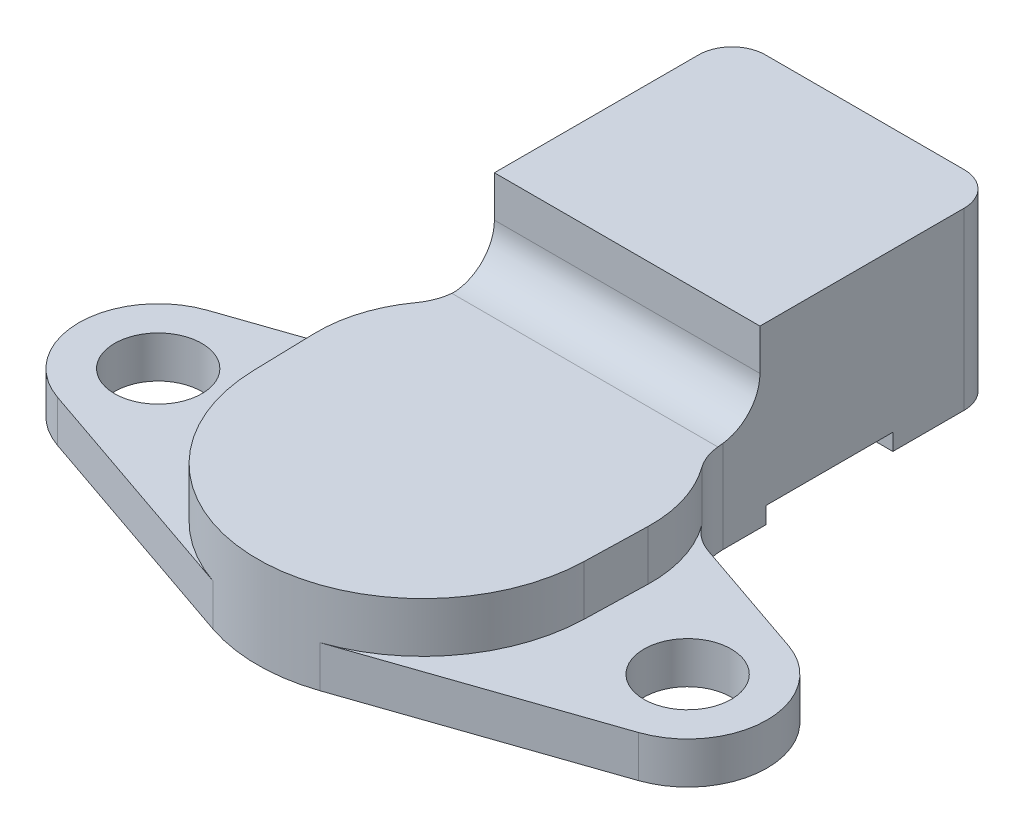
SolidWorks part; units mm, degrees
ref_plane "Front Plane" through (0, 0, 0) normal (0, 0, 1) x (1, 0, 0)
ref_plane "Top Plane" through (0, 0, 0) normal (0, 1, 0) x (1, 0, 0)
ref_plane "Right Plane" through (0, 0, 0) normal (1, 0, 0) x (0, 0, -1)
sketch "Sketch1" plane through (0, 0, 0) normal (0, 1, 0) x (1, 0, 0)
  line L30 (-6.7564, 4.8768) -> (-6.7564, 12.6)
  line L31 (-6.7564, 12.6) -> (-7.9629, 12.6)
  line L32 (-7.9629, 12.6) -> (-7.9629, 10.0193)
  line L33 (-10.1067, 7.0165) -> (-17.4219, 4.5043)
  line L34 (-17.4219, -4.5043) -> (-3.2216, -9.3809)
  line L35 (3.2216, -9.3809) -> (17.4219, -4.5043)
  line L36 (17.4219, 4.5043) -> (10.1067, 7.0165)
  line L37 (7.9629, 10.0193) -> (7.9629, 12.6)
  line L38 (7.9629, 12.6) -> (6.7564, 12.6)
  line L39 (6.7564, 12.6) -> (6.7564, 4.8768)
  line L46 (-6.7564, 20.22) -> (-6.7564, 24.25)
  line L47 (-6.7564, 24.25) -> (6.7564, 24.25)
  line L48 (6.7564, 24.25) -> (6.7564, 20.22)
  line L49 (6.7564, 20.22) -> (7.9629, 20.22)
  line L50 (7.9629, 20.22) -> (7.9629, 25.5)
  line L51 (7.9629, 25.5) -> (-7.9629, 25.5)
  line L52 (-7.9629, 25.5) -> (-7.9629, 20.22)
  line L53 (-7.9629, 20.22) -> (-6.7564, 20.22)
  circle A10 centre (15.875, 0) radius 2.6162
  circle A12 centre (-15.875, 0) radius 2.6162
  arc A28 (-6.7965, 4.8183) -> (-6.7564, 4.8768) centre (-8.6614, 6.1404) ccw
  arc A29 (-10.1067, 7.0165) -> (-7.9629, 10.0193) centre (-11.1379, 10.0193) ccw
  arc A30 (-17.4219, 4.5043) -> (-17.4219, -4.5043) centre (-15.875, 0) ccw
  arc A31 (-3.2216, -9.3809) -> (3.2216, -9.3809) centre (0, 0) ccw
  arc A32 (17.4219, -4.5043) -> (17.4219, 4.5043) centre (15.875, 0) ccw
  arc A33 (7.9629, 10.0193) -> (10.1067, 7.0165) centre (11.1379, 10.0193) ccw
  arc A34 (6.7564, 4.8768) -> (6.7965, 4.8183) centre (8.6614, 6.1404) ccw
  arc A35 (-6.7965, 4.8183) -> (6.7965, 4.8183) centre (0, 0) ccw
sketch "Sketch3" plane through (0, 0, 0) normal (0, 1, 0) x (1, 0, 0)
  line L0 (6.7564, 24.25) -> (6.7564, 20.22) construction
  line L1 (6.7564, 20.22) -> (7.9629, 20.22) construction
  line L2 (7.9629, 20.22) -> (7.9629, 25.5) construction
  line L3 (7.9629, 25.5) -> (-7.9629, 25.5) construction
  line L4 (-7.9629, 25.5) -> (-7.9629, 20.22) construction
  line L5 (-7.9629, 20.22) -> (-6.7564, 20.22) construction
  line L6 (-6.7564, 20.22) -> (-6.7564, 24.25) construction
  line L7 (-6.7564, 24.25) -> (6.7564, 24.25) construction
  line L8 (6.7564, 12.6) -> (6.7564, 4.8768) construction
  line L9 (7.9629, 12.6) -> (6.7564, 12.6) construction
  line L10 (7.9629, 10.0193) -> (7.9629, 12.6) construction
  line L11 (17.4219, 4.5043) -> (10.1067, 7.0165) construction
  line L12 (3.2216, -9.3809) -> (17.4219, -4.5043) construction
  line L13 (-17.4219, -4.5043) -> (-3.2216, -9.3809) construction
  line L14 (-10.1067, 7.0165) -> (-17.4219, 4.5043) construction
  line L15 (-7.9629, 12.6) -> (-7.9629, 10.0193) construction
  line L16 (-6.7564, 12.6) -> (-7.9629, 12.6) construction
  line L17 (-6.7564, 4.8768) -> (-6.7564, 12.6) construction
  line L18 (6.7564, 24.25) -> (6.7564, 20.22)
  line L19 (6.7564, 20.22) -> (7.9629, 20.22)
  line L20 (7.9629, 20.22) -> (7.9629, 25.5)
  line L21 (7.9629, 25.5) -> (-7.9629, 25.5)
  line L22 (-7.9629, 25.5) -> (-7.9629, 20.22)
  line L23 (-7.9629, 20.22) -> (-6.7564, 20.22)
  line L24 (-6.7564, 20.22) -> (-6.7564, 24.25)
  line L25 (-6.7564, 24.25) -> (6.7564, 24.25)
  line L26 (6.7564, 12.6) -> (6.7564, 4.8768)
  line L27 (7.9629, 12.6) -> (6.7564, 12.6)
  line L28 (7.9629, 10.0193) -> (7.9629, 12.6)
  line L29 (17.4219, 4.5043) -> (10.1067, 7.0165)
  line L30 (3.2216, -9.3809) -> (17.4219, -4.5043)
  line L31 (-17.4219, -4.5043) -> (-3.2216, -9.3809)
  line L32 (-10.1067, 7.0165) -> (-17.4219, 4.5043)
  line L33 (-7.9629, 12.6) -> (-7.9629, 10.0193)
  line L34 (-6.7564, 12.6) -> (-7.9629, 12.6)
  line L35 (-6.7564, 4.8768) -> (-6.7564, 12.6)
  circle A0 centre (-15.875, 0) radius 2.6162 construction
  circle A1 centre (15.875, 0) radius 2.6162 construction
  arc A2 (-6.7965, 4.8183) -> (6.7965, 4.8183) centre (0, 0) ccw construction
  arc A3 (6.7564, 4.8768) -> (6.7965, 4.8183) centre (8.6614, 6.1404) ccw construction
  arc A4 (7.9629, 10.0193) -> (10.1067, 7.0165) centre (11.1379, 10.0193) ccw construction
  arc A5 (17.4219, -4.5043) -> (17.4219, 4.5043) centre (15.875, 0) ccw construction
  arc A6 (-3.2216, -9.3809) -> (3.2216, -9.3809) centre (0, 0) ccw construction
  arc A7 (-17.4219, 4.5043) -> (-17.4219, -4.5043) centre (-15.875, 0) ccw construction
  arc A8 (-10.1067, 7.0165) -> (-7.9629, 10.0193) centre (-11.1379, 10.0193) ccw construction
  arc A9 (-6.7965, 4.8183) -> (-6.7564, 4.8768) centre (-8.6614, 6.1404) ccw construction
  circle A10 centre (-15.875, 0) radius 2.6162
  circle A11 centre (15.875, 0) radius 2.6162
  arc A12 (-6.7965, 4.8183) -> (6.7965, 4.8183) centre (0, 0) ccw
  arc A13 (6.7564, 4.8768) -> (6.7965, 4.8183) centre (8.6614, 6.1404) ccw
  arc A14 (7.9629, 10.0193) -> (10.1067, 7.0165) centre (11.1379, 10.0193) ccw
  arc A15 (17.4219, -4.5043) -> (17.4219, 4.5043) centre (15.875, 0) ccw
  arc A16 (-3.2216, -9.3809) -> (3.2216, -9.3809) centre (0, 0) ccw
  arc A17 (-17.4219, 4.5043) -> (-17.4219, -4.5043) centre (-15.875, 0) ccw
  arc A18 (-10.1067, 7.0165) -> (-7.9629, 10.0193) centre (-11.1379, 10.0193) ccw
  arc A19 (-6.7965, 4.8183) -> (-6.7564, 4.8768) centre (-8.6614, 6.1404) ccw
extrude "Boss-Extrude1" add sketch "Sketch3" along normal blind 1
sketch "Sketch4" plane through (0, 1, 0) normal (0, 1, 0) x (1, 0, 0)
  line L0 (-6.7564, 24.25) -> (6.7564, 24.25) construction
  line L1 (6.7564, 24.25) -> (6.7564, 20.22) construction
  line L3 (7.9629, 20.22) -> (7.9629, 25.5) construction
  line L4 (7.9629, 25.5) -> (-7.9629, 25.5) construction
  line L5 (-7.9629, 25.5) -> (-7.9629, 20.22) construction
  line L7 (-6.7564, 20.22) -> (-6.7564, 24.25) construction
  line L8 (-6.7564, 4.8768) -> (-6.7564, 12.6) construction
  line L10 (-7.9629, 12.6) -> (-7.9629, 10.0193) construction
  line L11 (-10.1067, 7.0165) -> (-17.4219, 4.5043) construction
  line L12 (-17.4219, -4.5043) -> (-3.2216, -9.3809) construction
  line L13 (3.2216, -9.3809) -> (17.4219, -4.5043) construction
  line L14 (17.4219, 4.5043) -> (10.1067, 7.0165) construction
  line L15 (7.9629, 10.0193) -> (7.9629, 12.6) construction
  line L17 (6.7564, 12.6) -> (6.7564, 4.8768) construction
  line L18 (-6.7564, 24.25) -> (6.7564, 24.25)
  line L19 (6.7564, 24.25) -> (6.7564, 20.22)
  line L21 (7.9629, 20.22) -> (7.9629, 25.5)
  line L22 (7.9629, 25.5) -> (-7.9629, 25.5)
  line L23 (-7.9629, 25.5) -> (-7.9629, 20.22)
  line L25 (-6.7564, 20.22) -> (-6.7564, 24.25)
  line L26 (-6.7564, 4.8768) -> (-6.7564, 12.6)
  line L28 (-7.9629, 12.6) -> (-7.9629, 10.0193)
  line L29 (-10.1067, 7.0165) -> (-17.4219, 4.5043)
  line L30 (-17.4219, -4.5043) -> (-3.2216, -9.3809)
  line L31 (3.2216, -9.3809) -> (17.4219, -4.5043)
  line L32 (17.4219, 4.5043) -> (10.1067, 7.0165)
  line L33 (7.9629, 10.0193) -> (7.9629, 12.6)
  line L35 (6.7564, 12.6) -> (6.7564, 4.8768)
  line L36 (7.9629, 12.6) -> (7.9629, 20.22)
  line L37 (6.7564, 20.22) -> (6.7564, 12.6)
  line L38 (-6.7564, 20.22) -> (-6.7564, 12.6)
  line L39 (-7.9629, 20.22) -> (-7.9629, 12.6)
  arc A0 (-6.7965, 4.8183) -> (-6.7564, 4.8768) centre (-8.6614, 6.1404) ccw construction
  circle A1 centre (15.875, 0) radius 2.6162
  circle A2 centre (15.875, 0) radius 2.6162
  circle A3 centre (-15.875, 0) radius 2.6162
  circle A4 centre (-15.875, 0) radius 2.6162
  arc A5 (-10.1067, 7.0165) -> (-7.9629, 10.0193) centre (-11.1379, 10.0193) ccw construction
  arc A6 (-17.4219, 4.5043) -> (-17.4219, -4.5043) centre (-15.875, 0) ccw construction
  arc A7 (-3.2216, -9.3809) -> (3.2216, -9.3809) centre (0, 0) ccw construction
  arc A8 (17.4219, -4.5043) -> (17.4219, 4.5043) centre (15.875, 0) ccw construction
  arc A9 (7.9629, 10.0193) -> (10.1067, 7.0165) centre (11.1379, 10.0193) ccw construction
  arc A10 (6.7564, 4.8768) -> (6.7965, 4.8183) centre (8.6614, 6.1404) ccw construction
  arc A11 (-6.7965, 4.8183) -> (6.7965, 4.8183) centre (0, 0) ccw construction
  arc A12 (-6.7965, 4.8183) -> (-6.7564, 4.8768) centre (-8.6614, 6.1404) ccw
  arc A13 (-10.1067, 7.0165) -> (-7.9629, 10.0193) centre (-11.1379, 10.0193) ccw
  arc A14 (-17.4219, 4.5043) -> (-17.4219, -4.5043) centre (-15.875, 0) ccw
  arc A15 (-3.2216, -9.3809) -> (3.2216, -9.3809) centre (0, 0) ccw
  arc A16 (17.4219, -4.5043) -> (17.4219, 4.5043) centre (15.875, 0) ccw
  arc A17 (7.9629, 10.0193) -> (10.1067, 7.0165) centre (11.1379, 10.0193) ccw
  arc A18 (6.7564, 4.8768) -> (6.7965, 4.8183) centre (8.6614, 6.1404) ccw
  arc A19 (-6.7965, 4.8183) -> (6.7965, 4.8183) centre (0, 0) ccw
  dimension "D1" = 0
  dimension "D2" = 0
extrude "Boss-Extrude2" add sketch "Sketch4" along normal blind 1.5
sketch "Sketch5" plane through (0, 2.5, 0) normal (0, 1, 0) x (1, 0, 0)
  line L0 (-9.9153, -0.2608) -> (-10.1067, 7.0165)
  line L1 (10.1067, 7.0165) -> (9.9153, -0.2608)
  line L3 (-6.7564, 24.25) -> (-6.7564, 4.8768)
  line L4 (6.7564, 24.25) -> (-6.7564, 24.25)
  line L5 (6.7564, 4.8768) -> (6.7564, 24.25)
  line L6 (-6.7564, 24.25) -> (-6.7564, 4.8768)
  line L7 (6.7564, 24.25) -> (-6.7564, 24.25)
  line L8 (6.7564, 4.8768) -> (6.7564, 24.25)
  line L15 (7.9629, 10.0193) -> (7.9629, 25.5)
  line L16 (7.9629, 25.5) -> (-7.9629, 25.5)
  line L17 (-7.9629, 25.5) -> (-7.9629, 10.0193)
  line L18 (-10.1067, 7.0165) -> (-17.4219, 4.5043)
  line L19 (-17.4219, -4.5043) -> (-3.2216, -9.3809)
  line L20 (3.2216, -9.3809) -> (17.4219, -4.5043)
  line L21 (17.4219, 4.5043) -> (10.1067, 7.0165)
  line L22 (7.9629, 10.0193) -> (7.9629, 25.5)
  line L23 (7.9629, 25.5) -> (-7.9629, 25.5)
  line L24 (-7.9629, 25.5) -> (-7.9629, 10.0193)
  line L25 (-10.1067, 7.0165) -> (-17.4219, 4.5043)
  line L26 (-17.4219, -4.5043) -> (-3.2216, -9.3809)
  line L27 (3.2216, -9.3809) -> (17.4219, -4.5043)
  line L28 (17.4219, 4.5043) -> (10.1067, 7.0165)
  arc A0 (-9.9153, -0.2608) -> (9.9153, -0.2608) centre (0, 0) ccw
  circle A1 centre (15.875, 0) radius 2.6162
  circle A2 centre (15.875, 0) radius 2.6162 construction
  arc A3 (-6.7965, 4.8183) -> (-6.7564, 4.8768) centre (-8.6614, 6.1404) ccw
  arc A4 (6.7564, 4.8768) -> (6.7965, 4.8183) centre (8.6614, 6.1404) ccw
  arc A5 (-6.7965, 4.8183) -> (6.7965, 4.8183) centre (0, 0) ccw
  arc A6 (-6.7965, 4.8183) -> (-6.7564, 4.8768) centre (-8.6614, 6.1404) ccw
  arc A7 (6.7564, 4.8768) -> (6.7965, 4.8183) centre (8.6614, 6.1404) ccw
  circle A9 centre (-15.875, 0) radius 2.6162
  circle A10 centre (-15.875, 0) radius 2.6162 construction
  arc A11 (-3.2216, -9.3809) -> (3.2216, -9.3809) centre (0, 0) ccw construction
  arc A17 (-10.1067, 7.0165) -> (-7.9629, 10.0193) centre (-11.1379, 10.0193) ccw
  arc A18 (-17.4219, 4.5043) -> (-17.4219, -4.5043) centre (-15.875, 0) ccw
  arc A19 (-3.2216, -9.3809) -> (3.2216, -9.3809) centre (0, 0) ccw
  arc A20 (17.4219, -4.5043) -> (17.4219, 4.5043) centre (15.875, 0) ccw
  arc A21 (7.9629, 10.0193) -> (10.1067, 7.0165) centre (11.1379, 10.0193) ccw
  arc A22 (-10.1067, 7.0165) -> (-7.9629, 10.0193) centre (-11.1379, 10.0193) ccw
  arc A23 (-17.4219, 4.5043) -> (-17.4219, -4.5043) centre (-15.875, 0) ccw
  arc A24 (-3.2216, -9.3809) -> (3.2216, -9.3809) centre (0, 0) ccw
  arc A25 (17.4219, -4.5043) -> (17.4219, 4.5043) centre (15.875, 0) ccw
  arc A26 (7.9629, 10.0193) -> (10.1067, 7.0165) centre (11.1379, 10.0193) ccw
  line M24 (7.9629, 10.0193) -> (7.9629, 25.5)
  line M25 (7.9629, 25.5) -> (-7.9629, 25.5)
  line M26 (-7.9629, 25.5) -> (-7.9629, 10.0193)
  arc M27 (-7.9629, 10.0193) -> (-10.1067, 7.0165) centre (-11.1379, 10.0193) cw
  arc M31 (-3.2216, -9.3809) -> (3.2216, -9.3809) centre (0, 0) ccw
  arc M35 (10.1067, 7.0165) -> (7.9629, 10.0193) centre (11.1379, 10.0193) cw
  arc M36 (-6.7965, 4.8183) -> (-6.7564, 4.8768) centre (-8.6614, 6.1404) ccw
  line M37 (-6.7564, 4.8768) -> (-6.7564, 24.25)
  line M38 (-6.7564, 24.25) -> (6.7564, 24.25)
  line M39 (6.7564, 24.25) -> (6.7564, 4.8768)
  arc M40 (6.7564, 4.8768) -> (6.7965, 4.8183) centre (8.6614, 6.1404) ccw
  arc M41 (6.7965, 4.8183) -> (-6.7965, 4.8183) centre (0, 0) cw
  dimension "D1" = 0
  dimension "D2" = 0
  dimension "D3" = 0
  dimension "D4" = 0
extrude "Boss-Extrude3" add sketch "Sketch5" along normal blind 3 contours A0 L1 L0 M31 M35 M24 M25 M26 M27 M41 M36 M37 M38 M39 M40 | M36 M41 M40 M39 M38 M37
sketch "Sketch6" plane through (0, 5.5, 0) normal (0, 1, 0) x (1, 0, 0)
  line L0 (-7.9629, 25.5) -> (-7.9629, 10.0193) construction
  line L1 (7.9629, 25.5) -> (-7.9629, 25.5)
  line L2 (7.9629, 25.5) -> (7.9629, 12.25)
  line L3 (7.9629, 12.25) -> (-7.9629, 12.25)
  line L4 (-7.9629, 25.5) -> (-7.9629, 12.25)
  dimension "D1" = 13.25
extrude "Boss-Extrude4" add sketch "Sketch6" along normal blind 5
sketch "Sketch7" plane through (0, 2.5, 0) normal (0, -1, 0) x (1, 0, 0)
  line L0 (-6.7564, -24.25) -> (-6.7564, -4.8768) construction
  line L1 (6.7564, -24.25) -> (-6.7564, -24.25)
  line L2 (6.7564, -24.25) -> (6.7564, -14.25)
  line L3 (6.7564, -14.25) -> (-6.7564, -14.25)
  line L4 (-6.7564, -24.25) -> (-6.7564, -14.25)
  dimension "D1" = 10
extrude "Cut-Extrude1" cut sketch "Sketch7" against normal blind 5
fillet "Fillet1" radius 2.54 1 edges at (-6.7564, 1.25, -4.8768)
fillet "Fillet2" radius 2.54 1 edges at (6.7564, 1.25, -4.8768)
fillet "Fillet3" radius 7.62 2 edges at (10.1067, 4, -7.0165) (-10.1067, 4, -7.0165)
fillet "Fillet5" radius 2.54 1 edges at (0, 5.5, -12.25)
sketch "Sketch8" plane through (0, 0, -25.5) normal (0, 0, -1) x (-1, 0, 0)
  line L0 (6.7564, 7.5) -> (-6.7564, 7.5) construction
  line L1 (6.7564, 7.5) -> (-6.7564, 7.5)
  line L4 (-7.9629, 0) -> (7.9629, 0)
  line L5 (7.9629, 0) -> (7.9629, 10.5)
  line L6 (7.9629, 10.5) -> (-7.9629, 10.5)
  line L8 (-7.9629, 0) -> (7.9629, 0)
  line L10 (7.9629, 10.5) -> (-7.9629, 10.5)
  line L16 (7.9629, 0) -> (7.9629, 10.5)
  line L18 (-7.9629, 10.5) -> (-7.9629, 0)
  line L19 (-7.9629, 10.5) -> (-7.9629, 0)
  dimension "D1" = 0
extrude "Cut-Extrude2" cut sketch "Sketch8" against normal blind 3
sketch "Sketch9" plane through (0, 0, -22.5) normal (0, 0, -1) x (-1, 0, 0)
  line L8 (-6.7564, 0) -> (-6.7564, 7.5)
  line L9 (-6.7564, 7.5) -> (6.7564, 7.5)
  line L10 (6.7564, 7.5) -> (6.7564, 0)
  line L11 (6.7564, 0) -> (7.9629, 0)
  line L12 (7.9629, 0) -> (7.9629, 10.5)
  line L13 (7.9629, 10.5) -> (-7.9629, 10.5)
  line L14 (-7.9629, 10.5) -> (-7.9629, 0)
  line L15 (-7.9629, 0) -> (-6.7564, 0)
  line L16 (-6.7564, 0) -> (-6.7564, 7.5)
  line L17 (-6.7564, 7.5) -> (6.7564, 7.5)
  line L18 (6.7564, 7.5) -> (6.7564, 0)
  line L19 (6.7564, 0) -> (7.9629, 0)
  line L20 (7.9629, 0) -> (7.9629, 10.5)
  line L21 (7.9629, 10.5) -> (-7.9629, 10.5)
  line L22 (-7.9629, 10.5) -> (-7.9629, 0)
  line L23 (-7.9629, 0) -> (-6.7564, 0)
  dimension "D1" = 0
extrude "Boss-Extrude5" add sketch "Sketch9" along normal blind 4
sketch "Sketch10" plane through (0, 0, -26.5) normal (0, 0, -1) x (-1, 0, 0)
  line L0 (0, 10.5) -> (0, 0) construction
  line L1 (7.9629, 10.5) -> (-7.9629, 10.5) construction
  line L2 (-6.7564, 7.5) -> (6.7564, 7.5) construction
  line L3 (-6.7564, 7.5) -> (-6.06, 7.5)
  line L4 (-6.7564, 7.5) -> (-6.7564, 0)
  line L5 (-6.7564, 0) -> (-6.06, 0)
  line L6 (-6.06, 7.5) -> (-6.06, 0)
  line L7 (6.06, 7.5) -> (6.7564, 7.5)
  line L8 (6.06, 7.5) -> (6.06, 0)
  line L9 (6.06, 0) -> (6.7564, 0)
  line L10 (6.7564, 7.5) -> (6.7564, 0)
  point P17 (-6.4082, 0)
  dimension "D1" = 12.12
  dimension "D2" = 6.06
extrude "Boss-Extrude6" add sketch "Sketch10" against normal blind 2
fillet "Fillet8" radius 2 2 edges at (-7.9629, 5.25, -26.5) (7.9629, 5.25, -26.5)
